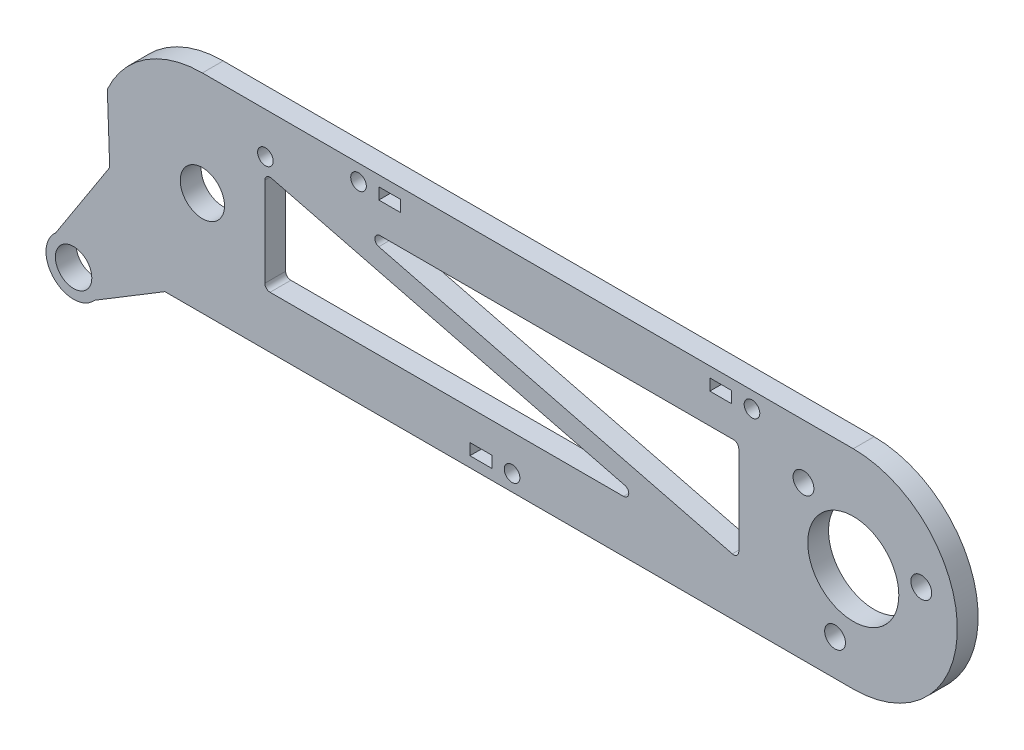
SolidWorks part; units mm, degrees
other "标注1"
sketch "草图6" plane through (-21, -34, 4) normal (0, 0, 1) x (1, 0, 0)
other "标注2"
sketch "草图7" plane through (-21, -34, 4) normal (0, 0, 1) x (1, 0, 0)
ref_plane "前视基准面" through (0, 0, 0) normal (0, 0, 1) x (1, 0, 0)
ref_plane "上视基准面" through (0, 0, 0) normal (0, 1, 0) x (1, 0, 0)
ref_plane "右视基准面" through (0, 0, 0) normal (1, 0, 0) x (0, 0, -1)
sketch "草图1" plane through (0, 0, 0) normal (0, 0, 1) x (1, 0, 0)
  line L7 (9, 12) -> (104.0643, -12) construction
  line L19 (-1, 0) -> (-1, -35) construction
  line L20 (-5, -35) -> (-17.2082, -11.7173) construction
  line L61 (3, -35) -> (10.0145, -20) construction
  line L63 (-1, 20) -> (-1, 17.12) construction
  line L67 (-1, 20) -> (124.0643, 20)
  line L68 (124.0643, -20) -> (10.0145, -20)
  line L71 (-1, -35) -> (-13.4774, -11.2038) construction
  line L73 (9, 12) -> (9, -12) construction
  line L74 (9, -12) -> (104.0643, -12) construction
  line L75 (104.0643, 12) -> (104.0643, -12) construction
  line L77 (32.8941, 8.0304) -> (100.8195, -9.1181)
  line L78 (102.0643, 9) -> (102.0643, -8.1485)
  line L79 (33.1389, 10) -> (101.0643, 10)
  line L80 (25.0926, 10) -> (102.0643, -9.4323) construction
  line L81 (25.0926, 10) -> (102.0643, 10) construction
  line L82 (102.0643, 10) -> (102.0643, -9.4323) construction
  line L83 (12.2448, 9.1181) -> (80.1702, -8.0304)
  line L84 (12, -10) -> (79.9254, -10)
  line L85 (11, 8.1485) -> (11, -9)
  line L86 (11, 9.4323) -> (87.9717, -10) construction
  line L87 (11, 9.4323) -> (11, -10) construction
  line L88 (11, -10) -> (87.9717, -10) construction
  line L105 (32.8941, 8.0304) -> (15.731, 12.3634) construction
  line L106 (33.1389, 10) -> (17.7488, 10) construction
  line L107 (32.9, 18) -> (37.1, 18)
  line L108 (101.0643, 10) -> (102.0643, 10) construction
  line L109 (102.0643, 10) -> (102.0643, 20) construction
  line L110 (32.9, 18) -> (32.9, 15.8)
  line L111 (32.9, 15.8) -> (37.1, 15.8)
  line L112 (37.1, 18) -> (37.1, 15.8)
  line L113 (29, 16.9) -> (32.9, 16.9) construction
  line L114 (100.7, 15.8) -> (96.5, 15.8)
  line L115 (100.7, 15.8) -> (100.7, 18)
  line L116 (100.7, 18) -> (96.5, 18)
  line L117 (96.5, 15.8) -> (96.5, 18)
  line L118 (104.6, 16.9) -> (100.7, 16.9) construction
  line L119 (-1, 20) -> (97.4837, 118.4837) construction
  line L120 (97.4837, 118.4837) -> (136.3875, 79.5799) construction
  line L121 (-21.7281, -28.2019) -> (-8.2015, -20)
  line L122 (-1, 0) -> (-45.4879, -44.4879) construction
  line L126 (-29.2019, -20.7281) -> (-18.8094, -4.651)
  line L127 (9, 12) -> (104.0643, 12) construction
  line L128 (-18.8094, -4.651) -> (-19.2648, 8.1485)
  line L129 (-8.2015, -20) -> (10.0145, -20)
  line L130 (54.6, -18) -> (50.4, -18)
  line L131 (54.6, -18) -> (54.6, -15.8)
  line L132 (54.6, -15.8) -> (50.4, -15.8)
  line L133 (50.4, -18) -> (50.4, -15.8)
  line L134 (58.5, -16.9) -> (54.6, -16.9) construction
  line L135 (37.1, 15.8) -> (50.4, 15.8) construction
  line L136 (50.4, 15.8) -> (50.4, -15.8) construction
  circle A0 centre (-1, 0) radius 4.25
  circle A13 centre (124.0643, 0) radius 8.75
  circle A18 centre (124.0643, 0) radius 13.53 construction
  arc A22 (124.0643, 20) -> (124.0643, -20) centre (124.0643, 0) cw
  circle A27 centre (114.4971, 9.5672) radius 2
  circle A28 centre (137.1333, 3.5018) radius 2
  circle A29 centre (120.5625, -13.069) radius 2
  circle A30 centre (-1, -35) radius 2 construction
  circle A31 centre (-1, -35) radius 4 construction
  arc A32 (-17.2082, -11.7173) -> (-1, 20) centre (-1, 0) cw construction
  arc A33 (-5, -35) -> (3, -35) centre (-1, -35) ccw construction
  arc A37 (32.8941, 8.0304) -> (33.1389, 10) centre (33.1389, 9) cw
  arc A38 (102.0643, 9) -> (101.0643, 10) centre (101.0643, 9) ccw
  arc A39 (102.0643, -8.1485) -> (100.8195, -9.1181) centre (101.0643, -8.1485) cw
  arc A40 (12.2448, 9.1181) -> (11, 8.1485) centre (12, 8.1485) ccw
  arc A41 (12, -10) -> (11, -9) centre (12, -9) cw
  arc A42 (79.9254, -10) -> (80.1702, -8.0304) centre (79.9254, -9) ccw
  circle A45 centre (29, 16.9) radius 1.5
  circle A46 centre (104.6, 16.9) radius 1.5
  circle A47 centre (-1, 0) radius 35 construction
  circle A48 centre (-25.7487, -24.7487) radius 3.5
  circle A49 centre (-25.7487, -24.7487) radius 5.3 construction
  arc A50 (-19.2648, 8.1485) -> (-1, 20) centre (-1, 0) cw
  arc A51 (-21.7281, -28.2019) -> (-29.2019, -20.7281) centre (-25.7487, -24.7487) cw
  circle A54 centre (11.1063, 12.1063) radius 1.5
  circle A55 centre (58.5, -16.9) radius 1.5
  dimension "D1" = 1
  dimension "D2" = 3
  dimension "D3" = 1
  dimension "D4" = 10
  dimension "D6" = 1
  dimension "D8" = 1
  dimension "D9" = 1
  dimension "D10" = 1
  dimension "D12" = 3
  dimension "D17" = 3
  dimension "D26" = 45
  dimension "D27" = 2.2
  dimension "D5" = 20
  dimension "D7" = 2
  dimension "D11" = 2.2
  dimension "D13" = 4.2
  dimension "D14" = 3.9
  dimension "D15" = 2
  dimension "D16" = 2.2
  dimension "D18" = 4.2
  dimension "D19" = 3.9
  dimension "D20" = 59.4
  dimension "D21" = 30
  dimension "D22" = 45
  dimension "D23" = 40
  dimension "D24" = 90
  dimension "D25" = 125.0643
extrude "凸台-拉伸1" add sketch "草图1" along normal blind 4
sketch "草图8" plane through (0, 0, 4) normal (0, 0, 1) x (1, 0, 0)
  circle A0 centre (-1, 0) radius 5
ref_point "点1"
